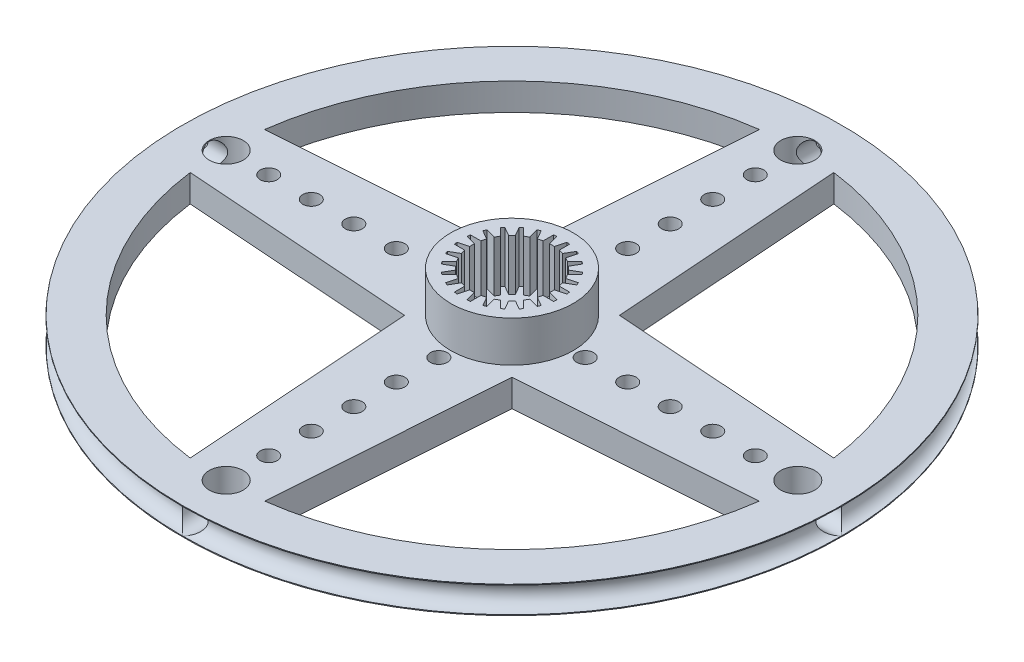
SolidWorks part; units mm, degrees
ref_plane "Plan de face" through (0, 0, 0) normal (0, 0, 1) x (1, 0, 0)
ref_plane "Plan de dessus" through (0, 0, 0) normal (0, 1, 0) x (1, 0, 0)
ref_plane "Plan de droite" through (0, 0, 0) normal (1, 0, 0) x (0, 0, -1)
sketch "Esquisse1" plane through (0, 0, 0) normal (0, 1, 0) x (1, 0, 0)
  circle A0 centre (0, 0) radius 3.75
  circle A1 centre (0, 0) radius 1.65
  dimension "D1" = 7.5
  dimension "D2" = 3.3
extrude "Boss.-Extru.1" add sketch "Esquisse1" along normal blind 4
sketch "Esquisse2" plane through (0, 4, 0) normal (0, 1, 0) x (1, 0, 0)
  line L0 (-3.25, 1.8708) -> (-2.1446, 17.3737)
  line L1 (2.1446, 17.3737) -> (3.25, 1.8708)
  line L2 (3.25, 1.8708) -> (-3.25, 1.8708)
  line L3 (-8.1717, 19.3708) -> (11.1602, 19.3708) construction
  circle A0 centre (0, 0) radius 3.75 construction
  arc A1 (-2.1446, 17.3737) -> (2.1446, 17.3737) centre (0, 17.2208) cw
  dimension "D3" = 2.15
  dimension "D1" = 6.5
  dimension "D2" = 17.5
extrude "Boss.-Extru.2" add sketch "Esquisse2" against normal up to surface (4 mm away) up to face at (0, 0, 3.75)
pattern_circular "Répétition circulaire1" count 4 over 360 about axis through (0, 0, 0) along (0, 1, 0) of "Boss.-Extru.2"
sketch "Esquisse3" plane through (0, 4, 0) normal (0, 1, 0) x (1, 0, 0)
  line L0 (0, 0) -> (0, 17.0578) construction
  circle A0 centre (0, 4.3) radius 0.5
  dimension "D1" = 1
  dimension "D2" = 4.3
extrude "Enlèv. mat.-Extru.1" cut sketch "Esquisse3" against normal blind 8
pattern_linear "Répétition linéaire1" count 6 spacing 2.5 along (0, 0, -1) of "Enlèv. mat.-Extru.1"
pattern_circular "Répétition circulaire2" count 4 over 360 about axis through (0, 0, 0) along (0, 1, 0) of "Enlèv. mat.-Extru.1", "Répétition linéaire1"
sketch "Esquisse4" plane through (0, 4, 0) normal (0, 1, 0) x (1, 0, 0)
  line L1 (-37.0652, 32.1232) -> (36.96, 32.1232)
  line L2 (-37.0652, 32.1232) -> (-37.0652, -32.9644)
  line L3 (-37.0652, -32.9644) -> (36.96, -32.9644)
  line L4 (36.96, 32.1232) -> (36.96, -32.9644)
  circle A0 centre (0, 0) radius 3.6
  dimension "D2" = 7.2
extrude "Enlèv. mat.-Extru.2" cut sketch "Esquisse4" against normal blind 2.4
sketch "Esquisse5" plane through (0, 4, 0) normal (0, 1, 0) x (1, 0, 0)
  circle A0 centre (0, 0) radius 2.95
  dimension "D1" = 5.9
extrude "Enlèv. mat.-Extru.3" cut sketch "Esquisse5" against normal blind 5
sketch "Sketch5" plane through (0, 0, 0) normal (0, -1, 0) x (1, 0, 0)
  circle A0 centre (0, 0) radius 2.95 construction
  circle A1 centre (0, 0) radius 2.95
  circle A2 centre (0, 0) radius 1.2
  dimension "D1" = 2.4
extrude "Boss-Extrude2" add sketch "Sketch5" against normal blind 1
sketch "Esquisse6" plane through (0, 4, 0) normal (0, 1, 0) x (1, 0, 0)
  line L0 (0, 0) -> (0, 3.6) construction
  line L2 (-2.0634, 2.95) -> (2.0634, 2.95) construction
  line L3 (-0.3, 2.95) -> (-0.1392, 2.35)
  line L4 (-0.1392, 2.35) -> (0.1392, 2.35)
  line L5 (0.1392, 2.35) -> (0.3, 2.95)
  line L6 (0.3, 2.95) -> (-0.3, 2.95)
  circle A0 centre (0, 0) radius 2.95 construction
  circle A1 centre (0, 0) radius 3.6 construction
  circle A2 centre (0, 0) radius 3.6 construction
  point P9 (0, 0)
  point P12 (0, 0)
  point P15 (0, 0)
  point P16 (0, 3.6)
  dimension "D1" = 0.6
  dimension "D2" = 0.6
  dimension "D3" = 15
extrude "Boss.-Extru.3" add sketch "Esquisse6" against normal up to surface (3 mm away) up to face at (0, 1, -1.2)
pattern_circular "Répétition circulaire3" count 24 over 360 about axis through (0, 0, 0) along (0, 1, 0) of "Boss.-Extru.3"
sketch "Sketch6" plane through (0, 0, 0) normal (0, -1, 0) x (1, 0, 0)
  circle A0 centre (0, 0) radius 2.45
  point P4 (0, 0)
  dimension "D1" = 4.9
extrude "Cut-Extrude2" cut sketch "Sketch6" against normal blind 0.6
sketch "Sketch7" plane through (0, 0, 0) normal (0, -1, 0) x (1, 0, 0)
  circle A0 centre (0, 0) radius 19.3708
  circle A2 centre (0, 0) radius 16.8708
  arc A5 (2.1446, 17.3737) -> (-2.1446, 17.3737) centre (0, 17.2208) ccw construction
  circle A6 centre (0, 16.8) radius 0.5 construction
  circle A7 centre (0, 16.8) radius 0.5
  circle A8 centre (16.8, 0) radius 0.5 construction
  circle A9 centre (16.8, 0) radius 0.5
  circle A10 centre (-16.8, 0) radius 0.5 construction
  circle A11 centre (-16.8, 0) radius 0.5
  circle A12 centre (0, -16.8) radius 0.5 construction
  circle A13 centre (0, -16.8) radius 0.5
  line M17 (-17.3737, -2.1446) -> (-3.1582, -3.1582)
  line M18 (-3.1582, -3.1582) -> (-2.1446, -17.3737)
  arc M19 (-2.1446, -17.3737) -> (2.1446, -17.3737) centre (0, -17.2208) ccw
  line M20 (2.1446, -17.3737) -> (3.1582, -3.1582)
  line M21 (3.1582, -3.1582) -> (17.3737, -2.1446)
  arc M22 (17.3737, -2.1446) -> (17.3737, 2.1446) centre (17.2208, 0) ccw
  line M23 (17.3737, 2.1446) -> (3.1582, 3.1582)
  line M24 (3.1582, 3.1582) -> (2.1446, 17.3737)
  arc M25 (2.1446, 17.3737) -> (-2.1446, 17.3737) centre (0, 17.2208) ccw
  line M26 (-2.1446, 17.3737) -> (-3.1582, 3.1582)
  line M27 (-3.1582, 3.1582) -> (-17.3737, 2.1446)
  arc M31 (-17.3737, 2.1446) -> (-17.3737, -2.1446) centre (-17.2208, 0) ccw
  dimension "D1" = 2.5
extrude "Boss-Extrude3" add sketch "Sketch7" against normal up to surface (1.6 mm away) contours A2 A0 M26 M25 M31 M27 | A2 A0 M17 M31 M19 M18 | A2 A0 M20 M19 M22 M21 | A2 A0 M23 M22 M25 M24 up to face at (0, 1.6, 0)
sketch "Sketch8" plane through (0, 0, 0) normal (0, 0, 1) x (1, 0, 0)
  line L1 (19.3708, 1.6) -> (19.3708, 0) construction
  line L2 (0, 0) -> (0, 4.0527) construction
  circle A0 centre (19.3708, 0.8) radius 0.75
  point P2 (19.3708, 0.8)
  dimension "D1" = 1.5
revolve "Cut-Revolve1" cut sketch "Sketch8" angle 360 about L2
ref_plane "Plane1" through (-19.3708, 0, 0) normal (-1, 0, 0) x (0, 0, 1)
sketch "Sketch9" plane through (-19.3708, 0, 0) normal (-1, 0, 0) x (0, 0, 1)
  line L0 (0, 0) -> (0, 1.6) construction
  line L1 (19.3708, 1.6) -> (-19.3708, 1.6) construction
  circle A0 centre (0, 0.8) radius 0.75
  dimension "D1" = 1.5
extrude "Cut-Extrude3" cut sketch "Sketch9" against normal blind 2.5
sketch "Sketch10" plane through (0, 0, 0) normal (0, -1, 0) x (1, 0, 0)
  circle A1 centre (-16.8, 0) radius 1
  circle A2 centre (-16.8, 0) radius 0.5 construction
  circle A3 centre (-16.8, 0) radius 0.5
  point P2 (0, 0)
  point P6 (0, 0)
  dimension "D1" = 0.5
extrude "Cut-Extrude4" cut sketch "Sketch10" against normal up to surface (1.6 mm away) up to face at (0, 1.6, 19.3708)
pattern_circular "CirPattern1" count 4 over 360 about axis through (0, 0, 0) along (0, 1, 0) of "Cut-Extrude3", "Cut-Extrude4"
